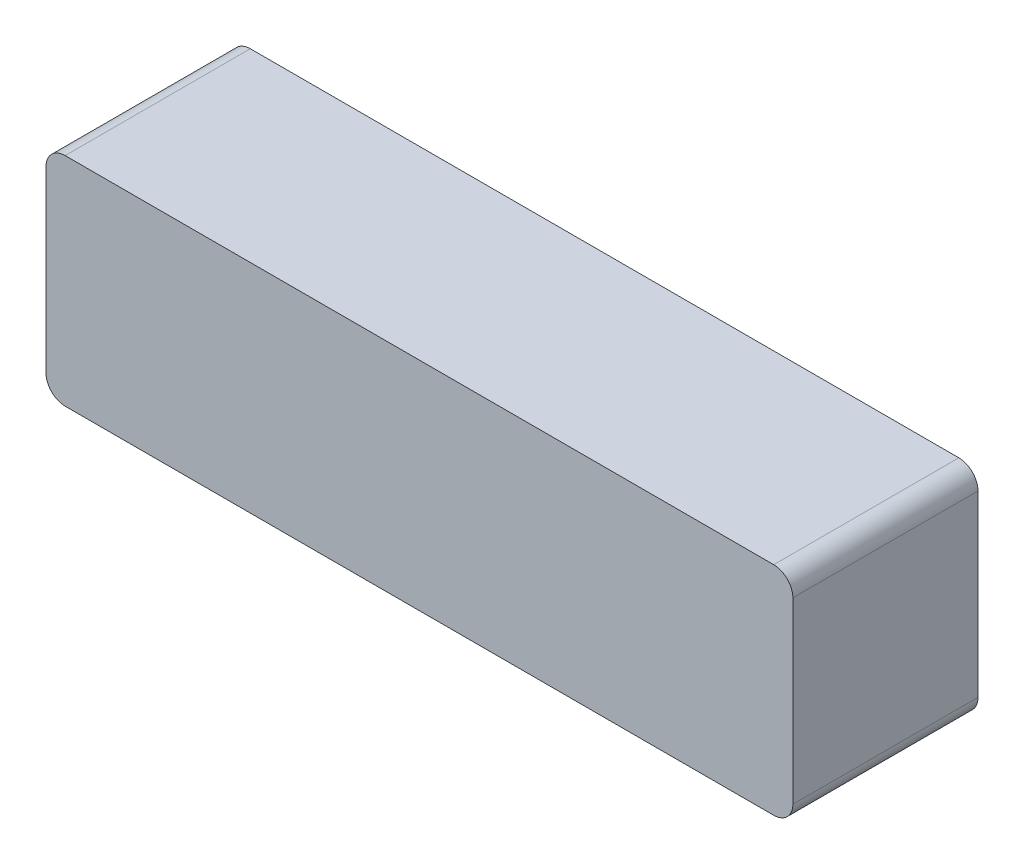
SolidWorks part; units mm, degrees
ref_plane "前视基准面" through (0, 0, 0) normal (0, 0, 1) x (1, 0, 0)
ref_plane "上视基准面" through (0, 0, 0) normal (0, 1, 0) x (1, 0, 0)
ref_plane "右视基准面" through (0, 0, 0) normal (1, 0, 0) x (0, 0, -1)
sketch "草图1" plane through (0, 0, 0) normal (0, 0, 1) x (1, 0, 0)
  line L1 (-55.5, -17) -> (55.5, -17)
  line L2 (-58.5, -14) -> (-58.5, 14)
  line L3 (-55.5, 17) -> (55.5, 17)
  line L4 (58.5, -14) -> (58.5, 14)
  line L5 (-58.5, -17) -> (58.5, 17) construction
  line L6 (-58.5, 17) -> (58.5, -17) construction
  arc A0 (55.5, 17) -> (58.5, 14) centre (55.5, 14) cw
  arc A1 (58.5, -14) -> (55.5, -17) centre (55.5, -14) cw
  arc A2 (-55.5, -17) -> (-58.5, -14) centre (-55.5, -14) cw
  arc A3 (-58.5, 14) -> (-55.5, 17) centre (-55.5, 14) cw
  point P0 (0, 0)
  dimension "D3" = 3
  dimension "D1" = 117
  dimension "D2" = 34
extrude "凸台-拉伸1" add sketch "草图1" along normal blind 29
